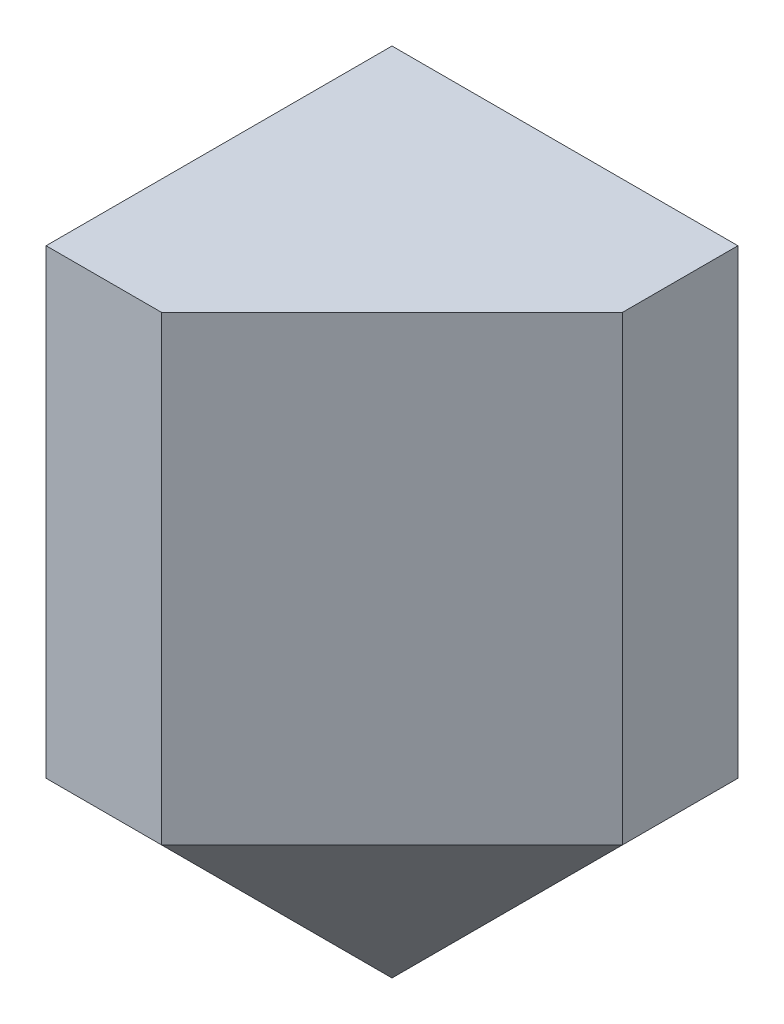
SolidWorks part; units mm, degrees
material "ABS"
ref_plane "Piano frontale" through (0, 0, 0) normal (0, 0, 1) x (1, 0, 0)
ref_plane "Piano superiore" through (0, 0, 0) normal (0, 1, 0) x (1, 0, 0)
ref_plane "Piano destro" through (0, 0, 0) normal (1, 0, 0) x (0, 0, -1)
sketch "Schizzo1" plane through (0, 0, 0) normal (0, 0, 1) x (1, 0, 0)
  line L1 (0, 0) -> (30, 0)
  line L2 (0, 0) -> (0, 40)
  line L3 (0, 40) -> (30, 40)
  line L4 (30, 0) -> (30, 40)
  dimension "D1" = 30
  dimension "D2" = 40
extrude "Estrusione-Estrusione1" add sketch "Schizzo1" along normal blind 30
chamfer "Smusso1" distance 20 angle 45 3 edges at (30, 20, 30) (30, 0, 15) (15, 0, 30)
sketch "Schizzo2" plane through (0, 40, 0) normal (0, 1, 0) x (1, 0, 0)
  line L0 (0, 0) -> (30, 0)
  line L1 (30, 0) -> (30, -10)
  line L2 (30, -10) -> (10, -30)
  line L3 (10, -30) -> (0, -30)
  line L4 (0, -30) -> (0, 0)
extrude "Estrusione-Estrusione2" add sketch "Schizzo2" along normal blind 20
hole_wizard "Foro per Vite M5-1" positions "Schizzo3" profile "Schizzo4" hole size "M5" standard "ISO"
sketch "Schizzo3" plane through (0, 0, 0) normal (-1, 0, 0) x (0, 0, 1)
  line L0 (18, 20) -> (18, 48) construction
  line L2 (0, 60) -> (0, 0) construction
  line L3 (0, 60) -> (30, 60) construction
  point P0 (18, 20)
  point P69 (18, 48)
  point P72 (18, 48)
  dimension "D1" = 18
  dimension "D2" = 12
  dimension "D3" = 28
sketch "Schizzo4" plane through (0, 20, 18) normal (0, 1, 0) x (0, 0, 1)
  line L0 (0, 0) -> (0, 14.6524)
  line L1 (0, 14.6524) -> (2.75, 13)
  line L2 (2.75, 13) -> (2.75, 0)
  line L5 (2.75, 0) -> (0, 0)
  line L10 (0, 14.6524) -> (-2.75, 13) construction
  line L11 (0, -6.35) -> (0, 107.95) construction
  dimension "Hole Dia." = 5.5
  dimension "Hole Depth" = 13
  dimension "Drill Angle" = 118
hole_wizard "Foro per Vite M5-2" positions "Schizzo3D1" profile "Schizzo5" hole size "M5" standard "ISO"
sketch3d "Schizzo3D1"
  line L0 (18, 20, 0) -> (18, 34, 0) construction
  line L2 (0, 60, 0) -> (0, 0, 0) construction
  line L4 (18, 48, 0) -> (18, 34, 0) construction
  line L8 (18, 48, 0) -> (14, 48, 0) construction
  line L10 (30, 60, 0) -> (0, 60, 0) construction
  point P2 (18, 20, 0)
  point P34 (14, 48, 0)
  point P42 (0, 0, 0)
  point P43 (14, 48, 0)
  dimension "D1" = 18
  dimension "D2" = 14
  dimension "D3" = 4
  dimension "D5" = 12
  dimension "D4" = 14
sketch "Schizzo5" plane through (18, 20, 0) normal (1, 0, 0) x (0, 1, 0)
  line L0 (0, 0) -> (0, 14.6524)
  line L1 (0, 14.6524) -> (2.75, 13)
  line L2 (2.75, 13) -> (2.75, 0)
  line L5 (2.75, 0) -> (0, 0)
  line L10 (0, 14.6524) -> (-2.75, 13) construction
  line L11 (0, -6.35) -> (0, 107.95) construction
  dimension "Hole Dia." = 5.5
  dimension "Hole Depth" = 13
  dimension "Drill Angle" = 118
